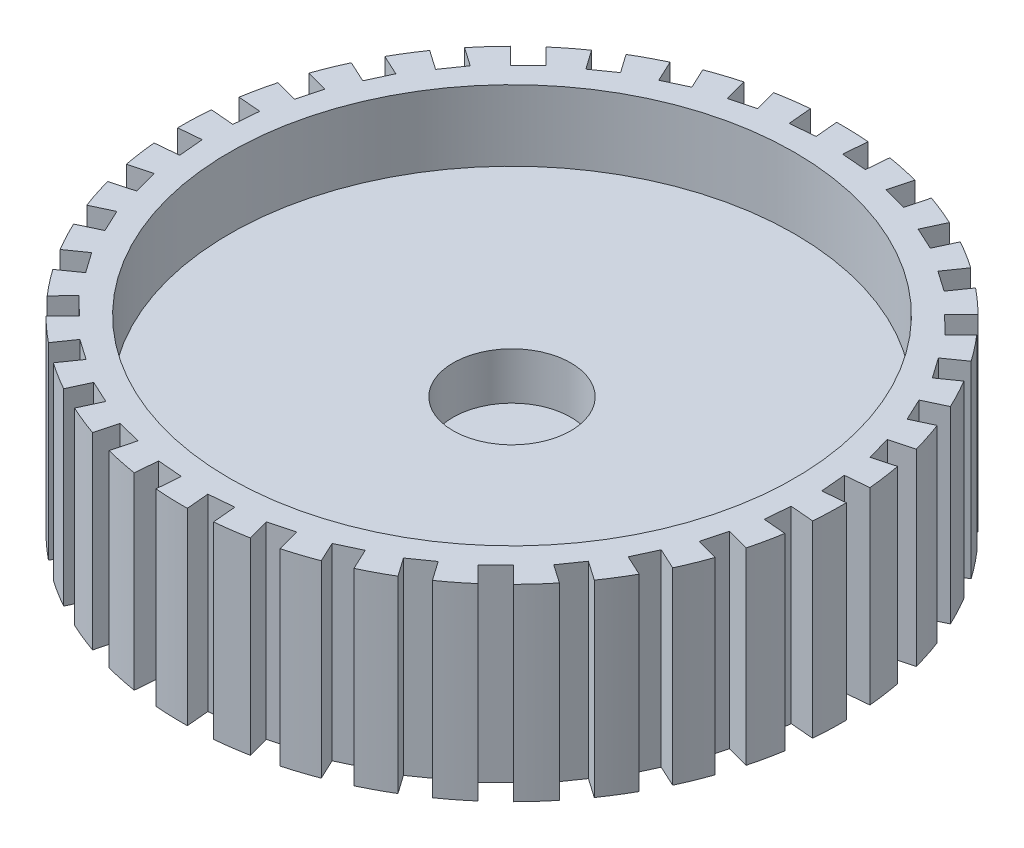
SolidWorks part; units mm, degrees
ref_plane "Front Plane" through (0, 0, 0) normal (0, 0, 1) x (1, 0, 0)
ref_plane "Top Plane" through (0, 0, 0) normal (0, 1, 0) x (1, 0, 0)
ref_plane "Right Plane" through (0, 0, 0) normal (1, 0, 0) x (0, 0, -1)
other "Configuration Table"
sketch "草图1" plane through (0, 0, 0) normal (0, 1, 0) x (1, 0, 0)
  circle A0 centre (0, 0) radius 13
  dimension "D1" = 26
extrude "凸台-拉伸1" add sketch "草图1" along normal blind 8
sketch "草图6" plane through (0, 8, 0) normal (0, 1, 0) x (1, 0, 0)
  circle A0 centre (0, 0) radius 14
  dimension "D1" = 28
extrude "凸台-拉伸4" add sketch "草图6" against normal through all
sketch "草图2" plane through (0, 8, 0) normal (0, 1, 0) x (1, 0, 0)
  circle A0 centre (0, 0) radius 12
  dimension "D1" = 24
extrude "切除-拉伸1" cut sketch "草图2" against normal blind 3
sketch "草图7" plane through (0, 8, 0) normal (0, 1, 0) x (1, 0, 0)
  line L0 (-15.6468, 4.1422) -> (-12.5671, 3.3269)
  line L1 (-15.6468, 4.1422) -> (-15.3762, 5.1646)
  line L2 (-12.5671, 3.3269) -> (-12.2964, 4.3493)
  line L3 (-15.3762, 5.1646) -> (-12.2964, 4.3493)
  line L4 (-14.6898, 6.7963) -> (-11.7985, 5.4586)
  line L5 (-14.6898, 6.7963) -> (-14.2457, 7.7562)
  line L6 (-14.2457, 7.7562) -> (-11.3544, 6.4185)
  line L7 (-11.7985, 5.4586) -> (-11.3544, 6.4185)
  line L8 (-13.2865, 9.2439) -> (-10.6713, 7.4245)
  line L9 (-13.2865, 9.2439) -> (-12.6825, 10.1121)
  line L10 (-12.6825, 10.1121) -> (-10.0673, 8.2926)
  line L11 (-10.6713, 7.4245) -> (-10.0673, 8.2926)
  line L12 (-11.4794, 11.4107) -> (-9.22, 9.1647)
  line L13 (-11.4794, 11.4107) -> (-10.7338, 12.1608)
  line L14 (-10.7338, 12.1608) -> (-8.4744, 9.9148)
  line L15 (-9.22, 9.1647) -> (-8.4744, 9.9148)
  line L16 (-9.3236, 13.2307) -> (-7.4884, 10.6265)
  line L17 (-9.3236, 13.2307) -> (-8.4591, 13.8399)
  line L18 (-8.4591, 13.8399) -> (-6.6239, 11.2358)
  line L19 (-7.4884, 10.6265) -> (-6.6239, 11.2358)
  line L20 (-6.8845, 14.6487) -> (-5.5294, 11.7654)
  line L21 (-6.8845, 14.6487) -> (-5.9273, 15.0986)
  line L22 (-5.9273, 15.0986) -> (-4.5722, 12.2153)
  line L23 (-5.5294, 11.7654) -> (-4.5722, 12.2153)
  line L24 (-4.2361, 15.6217) -> (-3.4024, 12.5469)
  line L25 (-4.2361, 15.6217) -> (-3.2154, 15.8985)
  line L26 (-3.2154, 15.8985) -> (-2.3816, 12.8237)
  line L27 (-3.4024, 12.5469) -> (-2.3816, 12.8237)
  line L28 (-1.4591, 16.1199) -> (-1.1719, 12.9471)
  line L29 (-1.4591, 16.1199) -> (-0.4058, 16.2153)
  line L30 (-0.4058, 16.2153) -> (-0.1186, 13.0424)
  line L31 (-1.1719, 12.9471) -> (-0.1186, 13.0424)
  line L32 (1.3622, 16.1284) -> (1.0941, 12.9539)
  line L33 (1.3622, 16.1284) -> (2.4161, 16.0394)
  line L34 (2.4161, 16.0394) -> (2.148, 12.8649)
  line L35 (1.0941, 12.9539) -> (2.148, 12.8649)
  line L36 (4.1422, 15.6468) -> (3.3269, 12.5671)
  line L37 (4.1422, 15.6468) -> (5.1646, 15.3762)
  line L38 (5.1646, 15.3762) -> (4.3493, 12.2964)
  line L39 (3.3269, 12.5671) -> (4.3493, 12.2964)
  line L40 (6.7963, 14.6898) -> (5.4586, 11.7985)
  line L41 (6.7963, 14.6898) -> (7.7562, 14.2457)
  line L42 (7.7562, 14.2457) -> (6.4185, 11.3544)
  line L43 (5.4586, 11.7985) -> (6.4185, 11.3544)
  line L44 (9.2439, 13.2865) -> (7.4245, 10.6713)
  line L45 (9.2439, 13.2865) -> (10.1121, 12.6825)
  line L46 (10.1121, 12.6825) -> (8.2926, 10.0673)
  line L47 (7.4245, 10.6713) -> (8.2926, 10.0673)
  line L48 (11.4107, 11.4794) -> (9.1647, 9.22)
  line L49 (11.4107, 11.4794) -> (12.1608, 10.7338)
  line L50 (12.1608, 10.7338) -> (9.9148, 8.4744)
  line L51 (9.1647, 9.22) -> (9.9148, 8.4744)
  line L52 (13.2307, 9.3236) -> (10.6265, 7.4884)
  line L53 (13.2307, 9.3236) -> (13.8399, 8.4591)
  line L54 (13.8399, 8.4591) -> (11.2358, 6.6239)
  line L55 (10.6265, 7.4884) -> (11.2358, 6.6239)
  line L56 (14.6487, 6.8845) -> (11.7654, 5.5294)
  line L57 (14.6487, 6.8845) -> (15.0986, 5.9273)
  line L58 (15.0986, 5.9273) -> (12.2153, 4.5722)
  line L59 (11.7654, 5.5294) -> (12.2153, 4.5722)
  line L60 (15.6217, 4.2361) -> (12.5469, 3.4024)
  line L61 (15.6217, 4.2361) -> (15.8985, 3.2154)
  line L62 (15.8985, 3.2154) -> (12.8237, 2.3816)
  line L63 (12.5469, 3.4024) -> (12.8237, 2.3816)
  line L64 (16.1199, 1.4591) -> (12.9471, 1.1719)
  line L65 (16.1199, 1.4591) -> (16.2153, 0.4058)
  line L66 (16.2153, 0.4058) -> (13.0424, 0.1186)
  line L67 (12.9471, 1.1719) -> (13.0424, 0.1186)
  line L68 (16.1284, -1.3622) -> (12.9539, -1.0941)
  line L69 (16.1284, -1.3622) -> (16.0394, -2.4161)
  line L70 (16.0394, -2.4161) -> (12.8649, -2.148)
  line L71 (12.9539, -1.0941) -> (12.8649, -2.148)
  line L72 (15.6468, -4.1422) -> (12.5671, -3.3269)
  line L73 (15.6468, -4.1422) -> (15.3762, -5.1646)
  line L74 (15.3762, -5.1646) -> (12.2964, -4.3493)
  line L75 (12.5671, -3.3269) -> (12.2964, -4.3493)
  line L76 (14.6898, -6.7963) -> (11.7985, -5.4586)
  line L77 (14.6898, -6.7963) -> (14.2457, -7.7562)
  line L78 (14.2457, -7.7562) -> (11.3544, -6.4185)
  line L79 (11.7985, -5.4586) -> (11.3544, -6.4185)
  line L80 (13.2865, -9.2439) -> (10.6713, -7.4245)
  line L81 (13.2865, -9.2439) -> (12.6825, -10.1121)
  line L82 (12.6825, -10.1121) -> (10.0673, -8.2926)
  line L83 (10.6713, -7.4245) -> (10.0673, -8.2926)
  line L84 (11.4794, -11.4107) -> (9.22, -9.1647)
  line L85 (11.4794, -11.4107) -> (10.7338, -12.1608)
  line L86 (10.7338, -12.1608) -> (8.4744, -9.9148)
  line L87 (9.22, -9.1647) -> (8.4744, -9.9148)
  line L88 (9.3236, -13.2307) -> (7.4884, -10.6265)
  line L89 (9.3236, -13.2307) -> (8.4591, -13.8399)
  line L90 (8.4591, -13.8399) -> (6.6239, -11.2358)
  line L91 (7.4884, -10.6265) -> (6.6239, -11.2358)
  line L92 (6.8845, -14.6487) -> (5.5294, -11.7654)
  line L93 (6.8845, -14.6487) -> (5.9273, -15.0986)
  line L94 (5.9273, -15.0986) -> (4.5722, -12.2153)
  line L95 (5.5294, -11.7654) -> (4.5722, -12.2153)
  line L96 (4.2361, -15.6217) -> (3.4024, -12.5469)
  line L97 (4.2361, -15.6217) -> (3.2154, -15.8985)
  line L98 (3.2154, -15.8985) -> (2.3816, -12.8237)
  line L99 (3.4024, -12.5469) -> (2.3816, -12.8237)
  line L100 (1.4591, -16.1199) -> (1.1719, -12.9471)
  line L101 (1.4591, -16.1199) -> (0.4058, -16.2153)
  line L102 (0.4058, -16.2153) -> (0.1186, -13.0424)
  line L103 (1.1719, -12.9471) -> (0.1186, -13.0424)
  line L104 (-1.3622, -16.1284) -> (-1.0941, -12.9539)
  line L105 (-1.3622, -16.1284) -> (-2.4161, -16.0394)
  line L106 (-2.4161, -16.0394) -> (-2.148, -12.8649)
  line L107 (-1.0941, -12.9539) -> (-2.148, -12.8649)
  line L108 (-4.1422, -15.6468) -> (-3.3269, -12.5671)
  line L109 (-4.1422, -15.6468) -> (-5.1646, -15.3762)
  line L110 (-5.1646, -15.3762) -> (-4.3493, -12.2964)
  line L111 (-3.3269, -12.5671) -> (-4.3493, -12.2964)
  line L112 (-6.7963, -14.6898) -> (-5.4586, -11.7985)
  line L113 (-6.7963, -14.6898) -> (-7.7562, -14.2457)
  line L114 (-7.7562, -14.2457) -> (-6.4185, -11.3544)
  line L115 (-5.4586, -11.7985) -> (-6.4185, -11.3544)
  line L116 (-9.2439, -13.2865) -> (-7.4245, -10.6713)
  line L117 (-9.2439, -13.2865) -> (-10.1121, -12.6825)
  line L118 (-10.1121, -12.6825) -> (-8.2926, -10.0673)
  line L119 (-7.4245, -10.6713) -> (-8.2926, -10.0673)
  line L120 (-11.4107, -11.4794) -> (-9.1647, -9.22)
  line L121 (-11.4107, -11.4794) -> (-12.1608, -10.7338)
  line L122 (-12.1608, -10.7338) -> (-9.9148, -8.4744)
  line L123 (-9.1647, -9.22) -> (-9.9148, -8.4744)
  line L124 (-13.2307, -9.3236) -> (-10.6265, -7.4884)
  line L125 (-13.2307, -9.3236) -> (-13.8399, -8.4591)
  line L126 (-13.8399, -8.4591) -> (-11.2358, -6.6239)
  line L127 (-10.6265, -7.4884) -> (-11.2358, -6.6239)
  line L128 (-14.6487, -6.8845) -> (-11.7654, -5.5294)
  line L129 (-14.6487, -6.8845) -> (-15.0986, -5.9273)
  line L130 (-15.0986, -5.9273) -> (-12.2153, -4.5722)
  line L131 (-11.7654, -5.5294) -> (-12.2153, -4.5722)
  line L132 (-15.6217, -4.2361) -> (-12.5469, -3.4024)
  line L133 (-15.6217, -4.2361) -> (-15.8985, -3.2154)
  line L134 (-15.8985, -3.2154) -> (-12.8237, -2.3816)
  line L135 (-12.5469, -3.4024) -> (-12.8237, -2.3816)
  line L136 (-16.1199, -1.4591) -> (-12.9471, -1.1719)
  line L137 (-16.1199, -1.4591) -> (-16.2153, -0.4058)
  line L138 (-16.2153, -0.4058) -> (-13.0424, -0.1186)
  line L139 (-12.9471, -1.1719) -> (-13.0424, -0.1186)
  line L140 (-16.1284, 1.3622) -> (-12.9539, 1.0941)
  line L141 (-16.1284, 1.3622) -> (-16.0394, 2.4161)
  line L142 (-16.0394, 2.4161) -> (-12.8649, 2.148)
  line L143 (-12.9539, 1.0941) -> (-12.8649, 2.148)
  circle A0 centre (0, 0) radius 13 construction
  point P150 (0, 0)
  dimension "D1" = 26
  dimension "D2" = 36
extrude "切除-拉伸2" cut sketch "草图7" against normal through all
sketch "草图8" plane through (0, 5, 0) normal (0, 1, 0) x (1, 0, 0)
  circle A0 centre (0, 0) radius 2.5
  dimension "D1" = 5
extrude "切除-拉伸3" cut sketch "草图8" against normal blind 2
